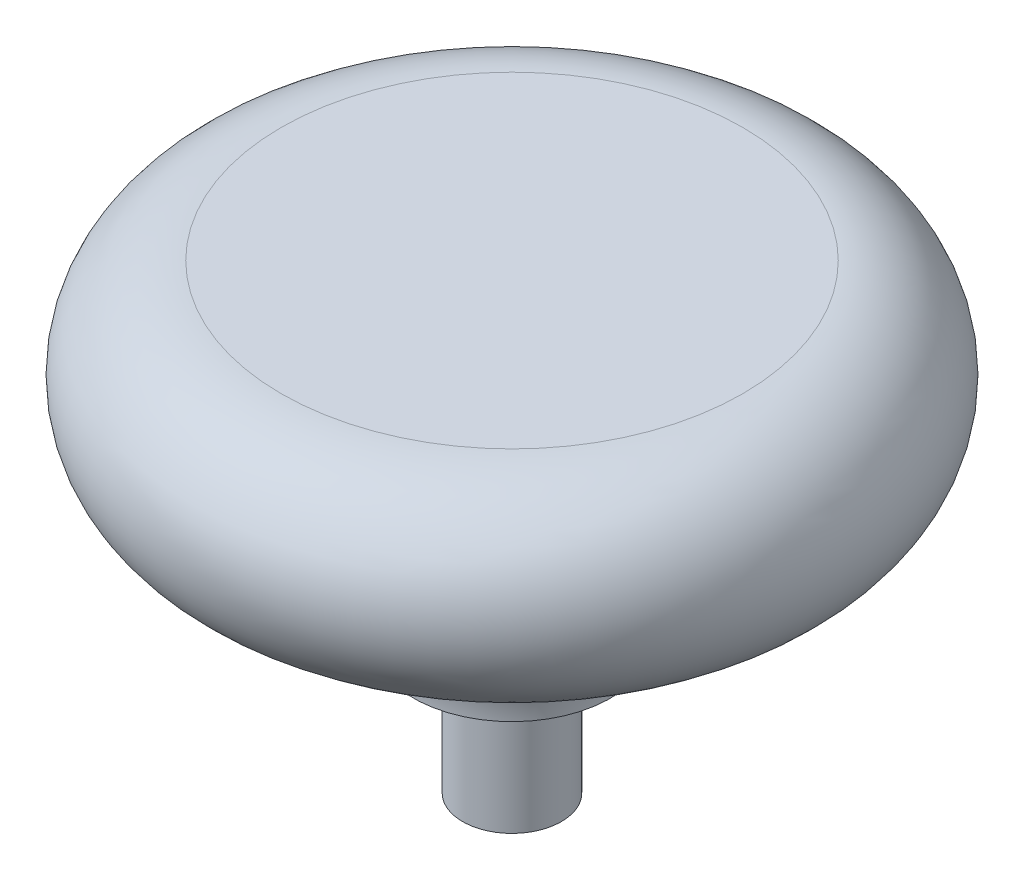
SolidWorks part; units mm, degrees
ref_plane "Front Plane" through (0, 0, 0) normal (0, 0, 1) x (1, 0, 0)
ref_plane "Top Plane" through (0, 0, 0) normal (0, 1, 0) x (1, 0, 0)
ref_plane "Right Plane" through (0, 0, 0) normal (1, 0, 0) x (0, 0, -1)
sketch "Sketch1" plane through (0, 0, 0) normal (0, 0, 1) x (1, 0, 0)
  line L0 (0, 0) -> (0, 31.6962) construction
  line L1 (0, 0) -> (2.38, 0)
  line L2 (2.38, 0) -> (2.38, 6.35)
  line L3 (2.38, 6.35) -> (4.765, 6.35)
  line L4 (11.115, 11.1364) -> (11.115, 23.7836) construction
  line L5 (15.5089, 17.46) -> (6.7211, 17.46) construction
  line L6 (11.115, 22.22) -> (0, 22.22)
  line L7 (0, 0) -> (0, 22.22)
  arc A0 (4.765, 6.35) -> (11.115, 12.7) centre (11.115, 6.35) cw
  arc A1 (11.115, 12.7) -> (11.115, 22.22) centre (11.115, 17.46) ccw
  point P13 (11.115, 17.46)
  dimension "D1" = 6.35
  dimension "D6" = 4.76
  dimension "D2" = 2.38
  dimension "D3" = 2.385
  dimension "D4" = 6.35
  dimension "D5" = 22.22
revolve "Revolve1" add sketch "Sketch1" angle 360 about L0
